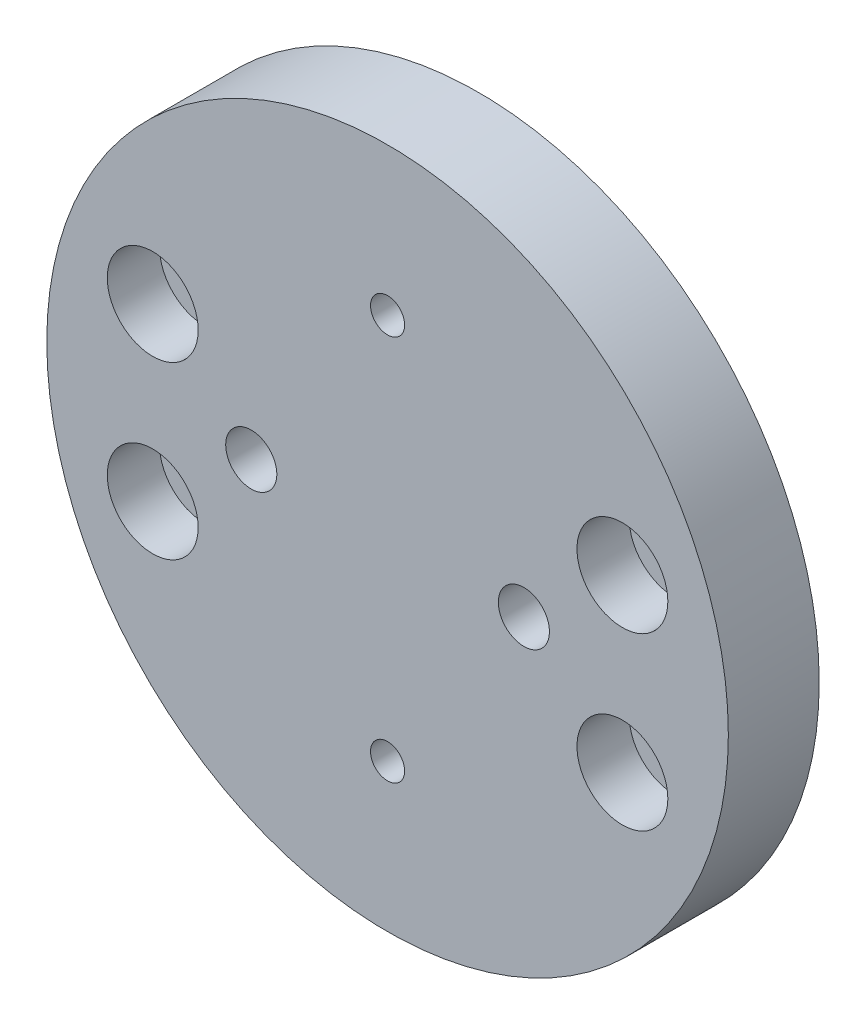
SolidWorks part; units mm, degrees
ref_plane "前视基准面" through (0, 0, 0) normal (0, 0, 1) x (1, 0, 0)
ref_plane "上视基准面" through (0, 0, 0) normal (0, 1, 0) x (1, 0, 0)
ref_plane "右视基准面" through (0, 0, 0) normal (1, 0, 0) x (0, 0, -1)
sketch "草图1" plane through (0, 0, 0) normal (0, 0, 1) x (1, 0, 0)
  circle A1 centre (0, 0) radius 30
  dimension "D1" = 60
extrude "凸台-拉伸1" add sketch "草图1" along normal blind 8
sketch "草图2" plane through (0, 0, 8) normal (0, 0, 1) x (1, 0, 0)
  line L0 (0, 15.75) -> (0, -15.75) construction
  line L1 (0, 0) -> (11.1369, -11.1369) construction
  circle A0 centre (0, 0) radius 15.75 construction
  dimension "D1" = 31.5
  dimension "D2" = 45
sketch "草图8" plane through (0, 0, 0) normal (0, 0, -1) x (-1, 0, 0)
  line L0 (12, 0) -> (-12, 0) construction
  line L1 (0, 17) -> (0, -17) construction
  line L2 (12, 0) -> (22, 0) construction
  line L3 (-12, 0) -> (-22, 0) construction
  line L4 (0, 0) -> (20.6732, 7.5244) construction
  arc A0 (20.6732, 7.5244) -> (22, 0) centre (0, 0) ccw construction
  point P6 (0, 0)
  dimension "D1" = 12
  dimension "D2" = 17
  dimension "D3" = 10
  dimension "D4" = 20
hole_wizard "打孔尺寸(%根据)内六角圆柱头螺钉的类型2" positions "草图9" profile "草图10" counterbore size "M4" standard "GB" end condition through all
sketch "草图9" plane through (0, 0, 0) normal (0, 0, -1) x (-1, 0, 0)
  point P0 (-12, 0)
  point P3 (12, 0)
sketch "草图10" plane through (12, 0, 0) normal (1, 0, 0) x (0, 1, 0)
  line L0 (0, 0) -> (0, 8)
  line L1 (0, 8) -> (2.25, 8)
  line L3 (2.25, 8) -> (2.25, 4.6)
  line L4 (4, 4.6) -> (2.25, 4.6)
  line L5 (4, 4.6) -> (4, 0.025)
  line L6 (4, 0.025) -> (4.025, 0)
  line L7 (4.025, 0) -> (0, 0)
  line L8 (-4, 0.025) -> (-4.025, 0) construction
  line L11 (0, -6.35) -> (0, 107.95) construction
  dimension "通孔孔直径" = 4.5
  dimension "通孔孔深度" = 8
  dimension "柱形沉头孔直径" = 8
  dimension "柱形沉头孔深度" = 4.6
  dimension "近端锥形沉头孔直径" = 8.05
  dimension "近端锥形沉头孔角度" = 90
hole_wizard "大小mm 暗销孔1" positions "草图11" profile "草图12" hole size "Ø3.0" standard "GB" end condition through all
sketch "草图11" plane through (0, 0, 0) normal (0, 0, -1) x (-1, 0, 0)
  point P0 (0, -17)
  point P3 (0, 17)
sketch "草图12" plane through (0, -17, 0) normal (1, 0, 0) x (0, 1, 0)
  line L0 (0, 0) -> (0, 8)
  line L1 (0, 8) -> (1.5, 8)
  line L2 (1.5, 8) -> (1.5, 0)
  line L5 (1.5, 0) -> (0, 0)
  line L11 (0, -6.35) -> (0, 107.95) construction
  dimension "通孔孔直径" = 3
  dimension "通孔孔深度" = 8
sketch "草图29" plane through (0, 0, 8) normal (0, 0, 1) x (1, 0, 0)
  line L0 (0, 0) -> (-20.6732, 7.5244) construction
  line L1 (-12, 0) -> (-22, 0) construction
  line L2 (0, 0) -> (-20.6732, 7.5244) construction
  line L3 (-12, 0) -> (-22, 0) construction
  line L4 (0, 0) -> (-20.6732, -7.5244) construction
  line L5 (0, 17) -> (0, -17) construction
  line L6 (0, 17) -> (0, -17) construction
  line L7 (0, 0) -> (20.6732, -7.5244) construction
  line L8 (0, 0) -> (20.6732, 7.5244) construction
  arc A0 (-22, 0) -> (-20.6732, 7.5244) centre (0, 0) ccw construction
  circle A1 centre (0, 0) radius 30
  circle A2 centre (0, 0) radius 30
  arc A3 (-22, 0) -> (-20.6732, 7.5244) centre (0, 0) ccw construction
  dimension "D1" = 0
hole_wizard "打孔尺寸(%根据)内六角圆柱头螺钉的类型3" positions "草图32" profile "草图33" counterbore size "M4" standard "GB" end condition through all
sketch "草图32" plane through (0, 0, 8) normal (0, 0, 1) x (1, 0, 0)
  point P0 (-20.6732, 7.5244)
  point P3 (-20.6732, -7.5244)
  point P6 (20.6732, 7.5244)
  point P9 (20.6732, -7.5244)
sketch "草图33" plane through (-20.6732, 7.5244, 8) normal (1, 0, 0) x (0, -1, 0)
  line L0 (0, 0) -> (0, 8)
  line L1 (0, 8) -> (2.25, 8)
  line L3 (2.25, 8) -> (2.25, 4.6)
  line L4 (2.25, 4.6) -> (4, 4.6)
  line L5 (4, 4.6) -> (4, 0)
  line L7 (4, 0) -> (0, 0)
  line L11 (0, -6.35) -> (0, 107.95) construction
  dimension "通孔孔直径" = 4.5
  dimension "通孔孔深度" = 8
  dimension "柱形沉头孔直径" = 8
  dimension "柱形沉头孔深度" = 4.6
